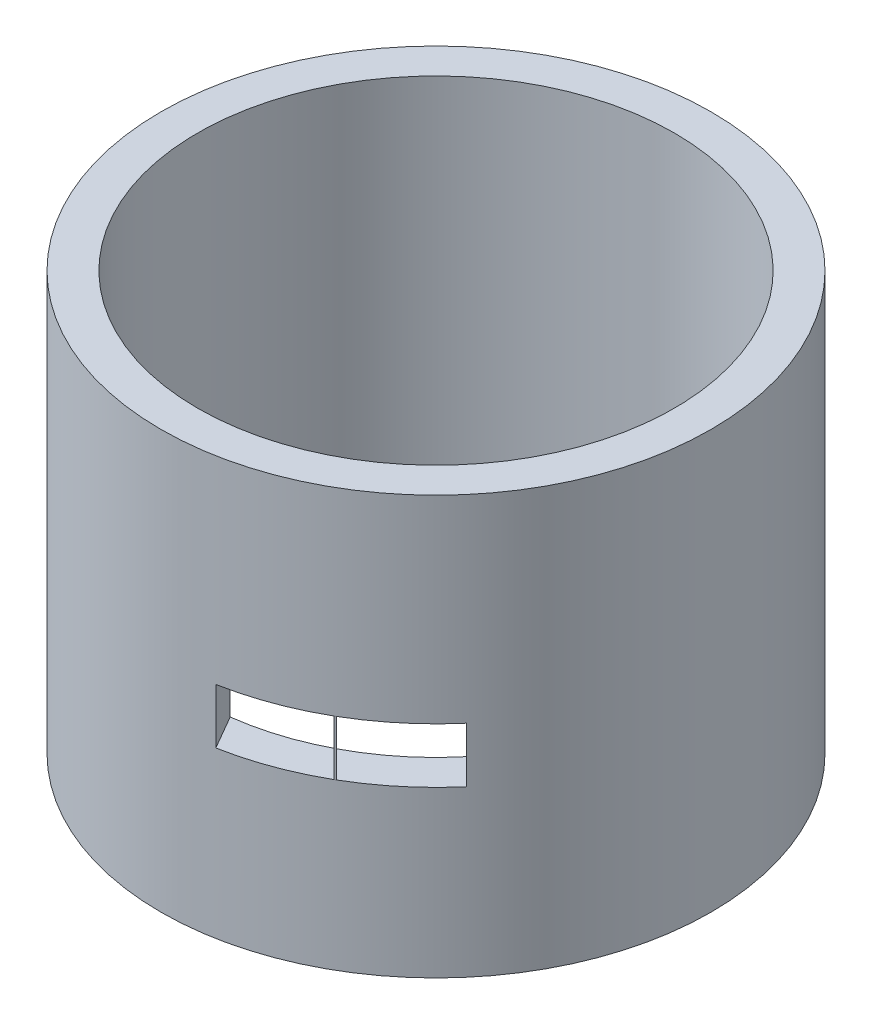
SolidWorks part; units mm, degrees
ref_plane "Front Plane" through (0, 0, 0) normal (0, 0, 1) x (1, 0, 0)
ref_plane "Top Plane" through (0, 0, 0) normal (0, 1, 0) x (1, 0, 0)
ref_plane "Right Plane" through (0, 0, 0) normal (1, 0, 0) x (0, 0, -1)
sketch "Sketch1" plane through (0, 0, 0) normal (0, 1, 0) x (1, 0, 0)
  circle A0 centre (0, 0) radius 75
extrude "Boss-Extrude1" add sketch "Sketch1" along normal blind 114
sketch "Sketch2" plane through (0, 114, 0) normal (0, 1, 0) x (1, 0, 0)
  circle A0 centre (0, 0) radius 65
extrude "Cut-Extrude1" cut sketch "Sketch2" against normal blind 120
sketch3d "3DSketch1"
  point P0 (37.744, 60.4689, 64.8104)
ref_plane "Plane1" through (37.4997, 0, 64.9514) normal (0.5, 0, 0.866) x (0.866, 0, -0.5)
sketch "Sketch3" plane through (37.4997, 0, 64.9514) normal (0.5, 0, 0.866) x (0.866, 0, -0.5)
  line L1 (-25, 60) -> (25, 60)
  line L2 (-25, 60) -> (-25, 45)
  line L3 (-25, 45) -> (25, 45)
  line L4 (25, 60) -> (25, 45)
extrude "Cut-Extrude2" cut sketch "Sketch3" against normal blind 15
